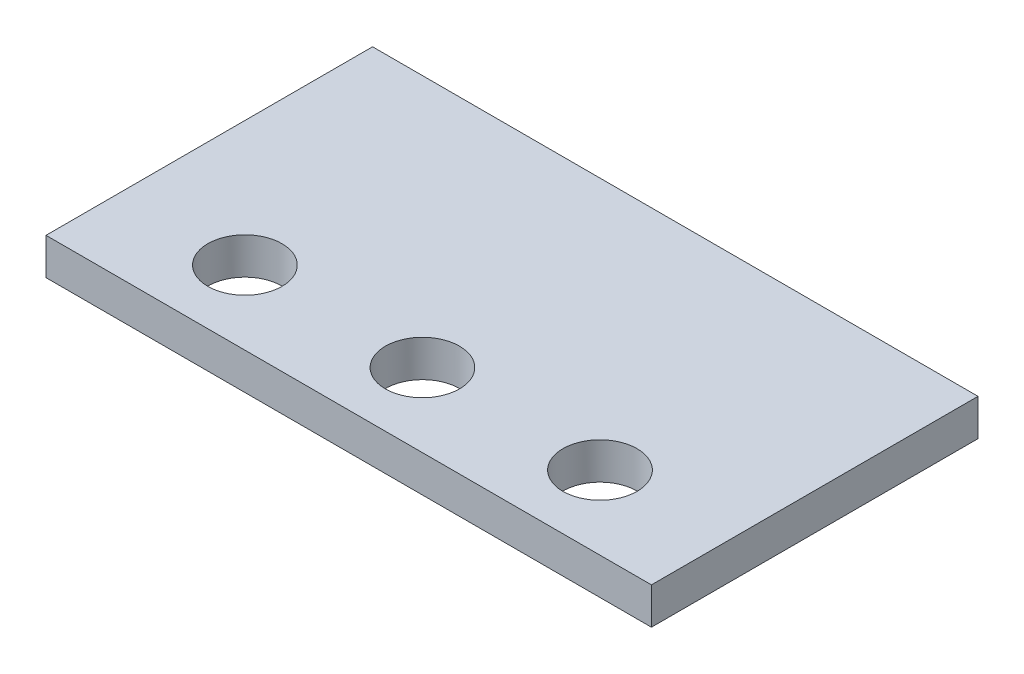
SolidWorks part; units mm, degrees
ref_plane "Alzado" through (0, 0, 0) normal (0, 0, 1) x (1, 0, 0)
ref_plane "Planta" through (0, 0, 0) normal (0, 1, 0) x (1, 0, 0)
ref_plane "Vista lateral" through (0, 0, 0) normal (1, 0, 0) x (0, 0, -1)
ref_plane "Plano2" through (0, 0, 360) normal (0, 0, -1) x (-1, 0, 0)
sketch "Croquis1" plane through (0, 0, 360) normal (0, 0, -1) x (-1, 0, 0)
  line L0 (-157.2459, -167.1656) -> (172.7541, -167.1656)
  line L1 (-177.2459, -167.1656) -> (192.7541, -167.1656) construction
  line L2 (7.7541, -167.1656) -> (7.7541, -33.1806) construction
  line L4 (-157.2459, -167.1656) -> (172.7541, -167.1656)
  line L5 (-157.2459, -167.1656) -> (-157.2459, -147.1656)
  line L6 (-157.2459, -147.1656) -> (172.7541, -147.1656)
  line L7 (172.7541, -167.1656) -> (172.7541, -147.1656)
  point P5 (7.7541, -167.1656)
  dimension "D1" = 330
  dimension "D2" = 20
extrude "Saliente-Extruir1" add sketch "Croquis1" along normal blind 178 contours L0 L2 L6 L5 | L2 L4 L7 L6
sketch "Croquis2" plane through (0, -167.1656, 0) normal (0, -1, 0) x (1, 0, 0)
  line L0 (-7.7541, 360) -> (-7.7541, 340) construction
  line L2 (157.2459, 360) -> (-172.7541, 360) construction
  circle A0 centre (-104.5195, 319.8097) radius 20.1903
  circle A1 centre (-7.7541, 319.8097) radius 20.1903
  circle A2 centre (89.0113, 319.8097) radius 20.1903
  dimension "D1" = 20
  dimension "D2" = 3
extrude "Cortar-Extruir1" cut sketch "Croquis2" against normal up to next contours A2 | A1 | A0
